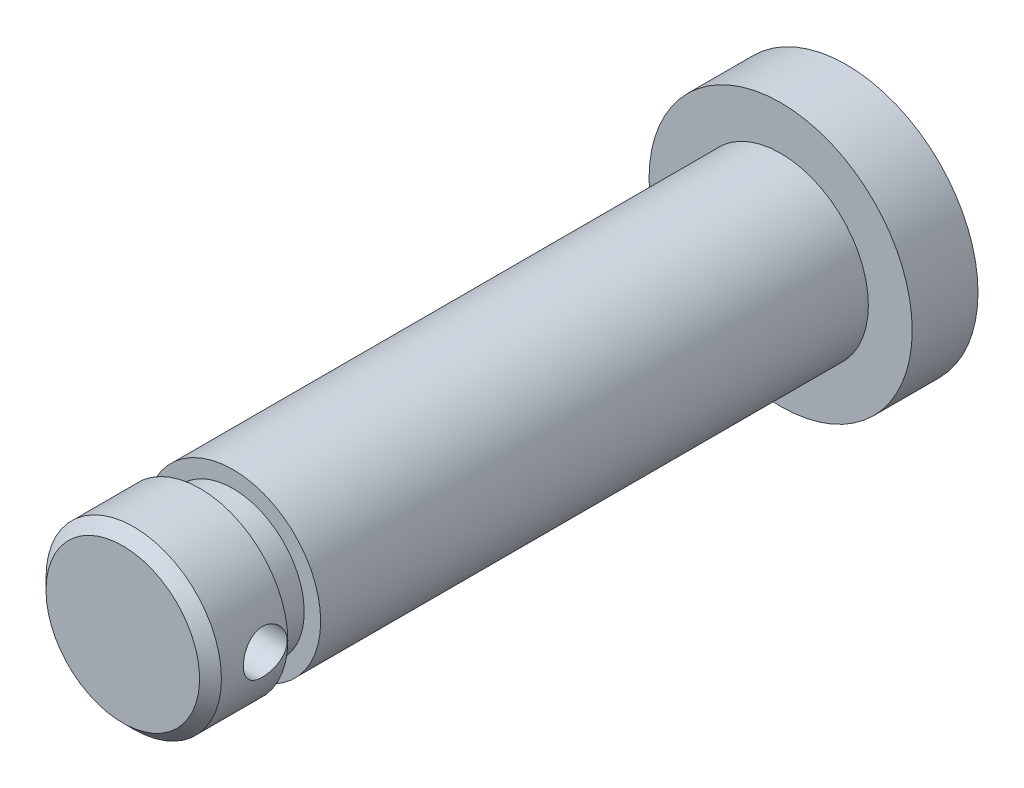
SolidWorks part; units mm, degrees
ref_plane "前视基准面" through (0, 0, 0) normal (0, 0, 1) x (1, 0, 0)
ref_plane "上视基准面" through (0, 0, 0) normal (0, 1, 0) x (1, 0, 0)
ref_plane "右视基准面" through (0, 0, 0) normal (1, 0, 0) x (0, 0, -1)
ref_plane "基准面1" through (9, 0, 0) normal (1, 0, 0) x (0, 0, -1)
ref_plane "基准面2" through (12, 0, 0) normal (1, 0, 0) x (0, 0, -1)
sketch "草图8" plane through (0, 0, 0) normal (0, 1, 0) x (1, 0, 0)
  line L0 (0, 0) -> (0, -66) construction
  line L1 (0, 0) -> (12, 0)
  line L2 (12, 0) -> (12, -6)
  line L3 (12, -6) -> (8, -6)
  line L4 (8, -6) -> (8, -65)
  line L5 (8, -65) -> (7, -66)
  line L6 (7, -66) -> (0, -66)
  line L7 (0, -66) -> (0, 0)
revolve "旋转2" add sketch "草图8" angle 360 about L0
sketch "草图9" plane through (9, 0, 0) normal (1, 0, 0) x (0, 0, -1)
  circle A0 centre (-61, 0) radius 2
extrude "切除-拉伸12" cut sketch "草图9" against normal blind 20
ref_plane "基准面3" through (0, 0, 56) normal (0, 0, 1) x (1, 0, 0)
sketch "草图13" plane through (0, 0, 0) normal (0, 1, 0) x (1, 0, 0)
  line L0 (0, 0) -> (0, -66) construction
  line L1 (6.5, -55.95) -> (8.5, -55.95)
  line L2 (8.5, -55.95) -> (8.5, -58.95)
  line L3 (8.5, -58.95) -> (6.5, -58.95)
  line L4 (6.5, -58.95) -> (6.5, -55.95)
revolve "切除-旋转3" cut sketch "草图13" angle 360 about L0
